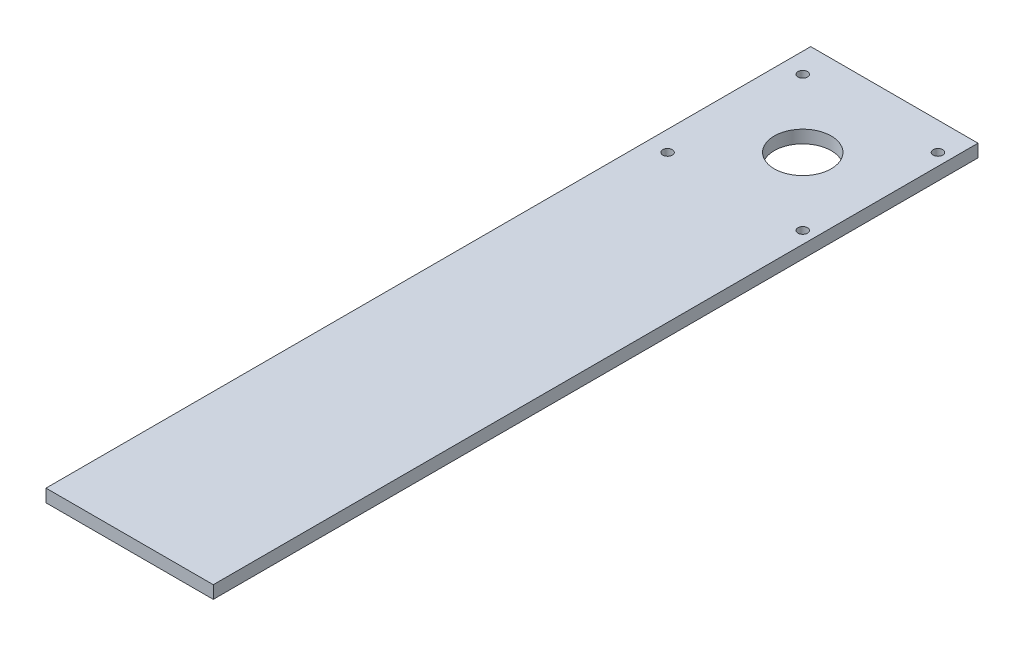
SolidWorks part; units mm, degrees
ref_plane "Front Plane" through (0, 0, 0) normal (0, 0, 1) x (1, 0, 0)
ref_plane "Top Plane" through (0, 0, 0) normal (0, 1, 0) x (1, 0, 0)
ref_plane "Right Plane" through (0, 0, 0) normal (1, 0, 0) x (0, 0, -1)
sketch "Sketch1" plane through (0, 0, 0) normal (0, 1, 0) x (1, 0, 0)
  line L0 (0, 240) -> (0, -240) construction
  line L1 (-55, -240) -> (50, -240)
  line L2 (-55, -240) -> (-55, 240)
  line L3 (-55, 240) -> (50, 240)
  line L4 (50, -240) -> (50, 240)
  line L5 (95, 240) -> (95, -240) construction
  line L6 (-55, 105.3959) -> (50, 105.3959) construction
  line L7 (-44.628, 240) -> (-44.628, -240) construction
  line L8 (38.5879, 240) -> (38.5879, -240) construction
  line L9 (-55, -78.4291) -> (50, -78.4291) construction
  line L10 (-42.4264, 137.5736) -> (0, 180) construction
  circle A0 centre (0, 180) radius 50 construction
  circle A1 centre (0, 180) radius 17.8616
  circle A2 centre (-42.4264, 137.5736) radius 3
  circle A3 centre (-42.4264, 222.4264) radius 3
  circle A4 centre (42.4264, 222.4264) radius 3
  circle A5 centre (42.4264, 137.5736) radius 3
  point P22 (33.1525, 121.5384)
  point P23 (0, 168)
  point P24 (95, -240)
  point P31 (0, 180)
  dimension "D1" = 100
  dimension "D2" = 95
  dimension "D10" = 6
  dimension "D3" = 150
  dimension "D4" = 480
  dimension "D5" = 45
  dimension "D6" = 60
  dimension "D7" = 105
  dimension "D8" = 60
  dimension "D9" = 45
  dimension "D11" = 4
extrude "Boss-Extrude1" add sketch "Sketch1" along normal blind 8
